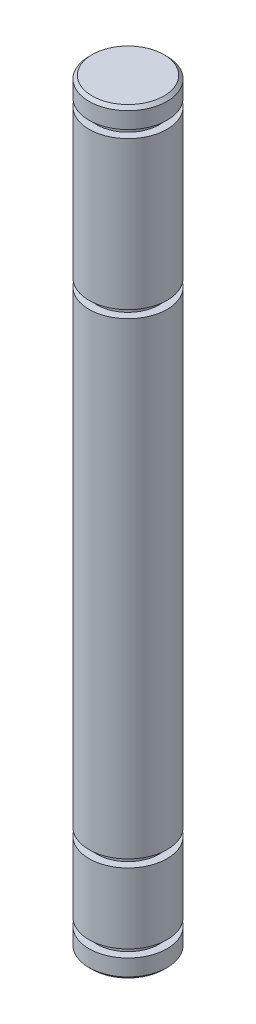
SolidWorks part; units mm, degrees
ref_plane "Front" through (0, 0, 0) normal (0, 0, 1) x (1, 0, 0)
ref_plane "Top" through (0, 0, 0) normal (0, 1, 0) x (1, 0, 0)
ref_plane "Right" through (0, 0, 0) normal (1, 0, 0) x (0, 0, -1)
sketch "Sketch1" plane through (0, 0, 0) normal (0, 0, 1) x (1, 0, 0)
  line L0 (6.35, 61.087) -> (5.842, 61.595)
  line L1 (5.842, -61.595) -> (0, -61.595)
  line L2 (6.35, -61.087) -> (6.35, -58.42)
  line L3 (5.842, 61.595) -> (0, 61.595)
  line L4 (0, -61.595) -> (0, 61.595)
  line L5 (6.35, -61.087) -> (5.842, -61.595)
  line L6 (6.35, 58.42) -> (6.35, 61.087)
  line L7 (6.35, 58.42) -> (5.08, 58.42)
  line L8 (6.35, -57.15) -> (6.35, -45.72)
  line L9 (6.35, 57.15) -> (5.08, 57.15)
  line L10 (5.08, 58.42) -> (5.08, 57.15)
  line L11 (6.35, -58.42) -> (5.08, -58.42)
  line L12 (6.35, 33.02) -> (6.35, 57.15)
  line L13 (6.35, -57.15) -> (5.08, -57.15)
  line L14 (5.08, -58.42) -> (5.08, -57.15)
  line L15 (6.35, 33.02) -> (5.08, 33.02)
  line L16 (6.35, -44.45) -> (6.35, 31.75)
  line L17 (6.35, 31.75) -> (5.08, 31.75)
  line L18 (5.08, 33.02) -> (5.08, 31.75)
  line L23 (6.35, -44.45) -> (5.08, -44.45)
  line L25 (6.35, -45.72) -> (5.08, -45.72)
  line L26 (5.08, -44.45) -> (5.08, -45.72)
  point P0 (6.35, -61.595)
  point P2 (6.35, 61.595)
  point P4 (0, 0)
  dimension "D2" = 6.35
  dimension "D5" = 0.508
  dimension "D6" = 0.508
  dimension "D3" = 3.175
  dimension "D4" = 1.27
  dimension "D7" = 1.27
  dimension "D8" = 3.175
  dimension "D10" = 25.4
  dimension "D11" = 76.2
  dimension "D12" = 12.7
revolve "Revolve1" add sketch "Sketch1" angle 360 about L4
